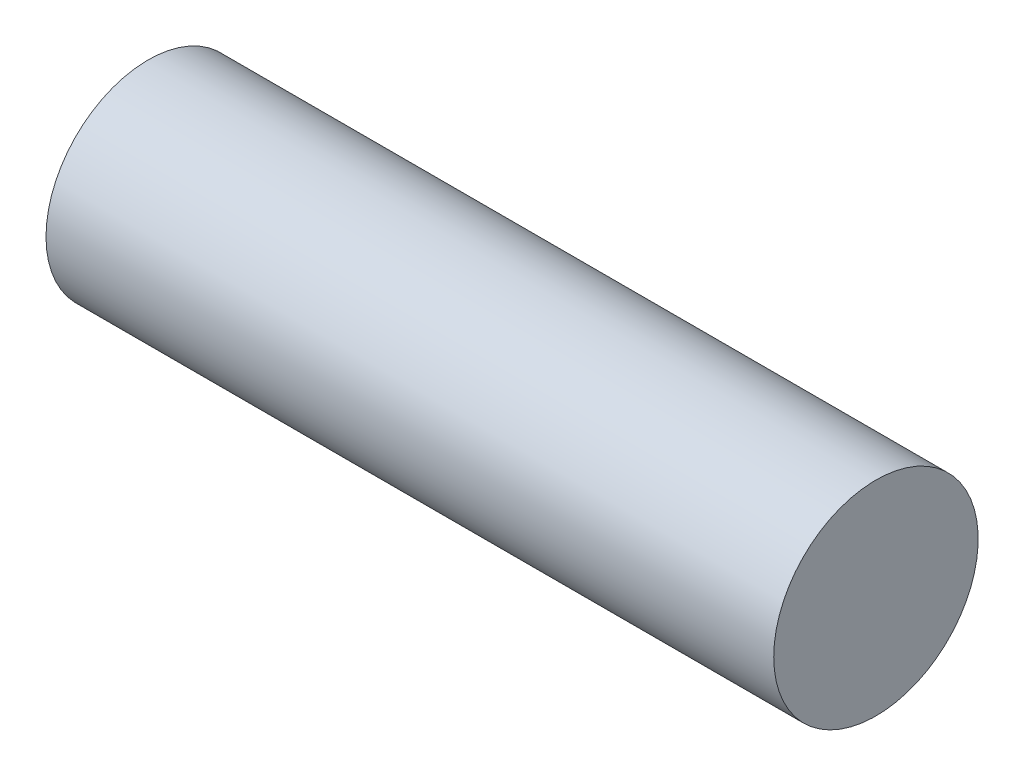
SolidWorks part; units mm, degrees
ref_plane "Plan de face" through (0, 0, 0) normal (0, 0, 1) x (1, 0, 0)
ref_plane "Plan de dessus" through (0, 0, 0) normal (0, 1, 0) x (1, 0, 0)
ref_plane "Plan de droite" through (0, 0, 0) normal (1, 0, 0) x (0, 0, -1)
sketch "Esquisse1" plane through (0, 0, 0) normal (0, 0, 1) x (1, 0, 0)
  line L0 (-19.1719, 44.271) -> (-334.3611, 44.271) construction
  line L1 (-19.1719, 44.271) -> (-334.3611, 44.271)
  line L2 (-334.3611, 44.271) -> (-334.3611, 0)
  line L3 (-334.3611, -44.271) -> (-334.3611, 44.271) construction
  line L4 (-334.3611, 0) -> (-19.1719, 0)
  line L5 (-19.1719, 44.271) -> (-19.1719, -44.271) construction
  line L6 (-19.1719, 0) -> (-19.1719, 44.271)
revolve "Révolution1" add sketch "Esquisse1" angle 360 about L4
